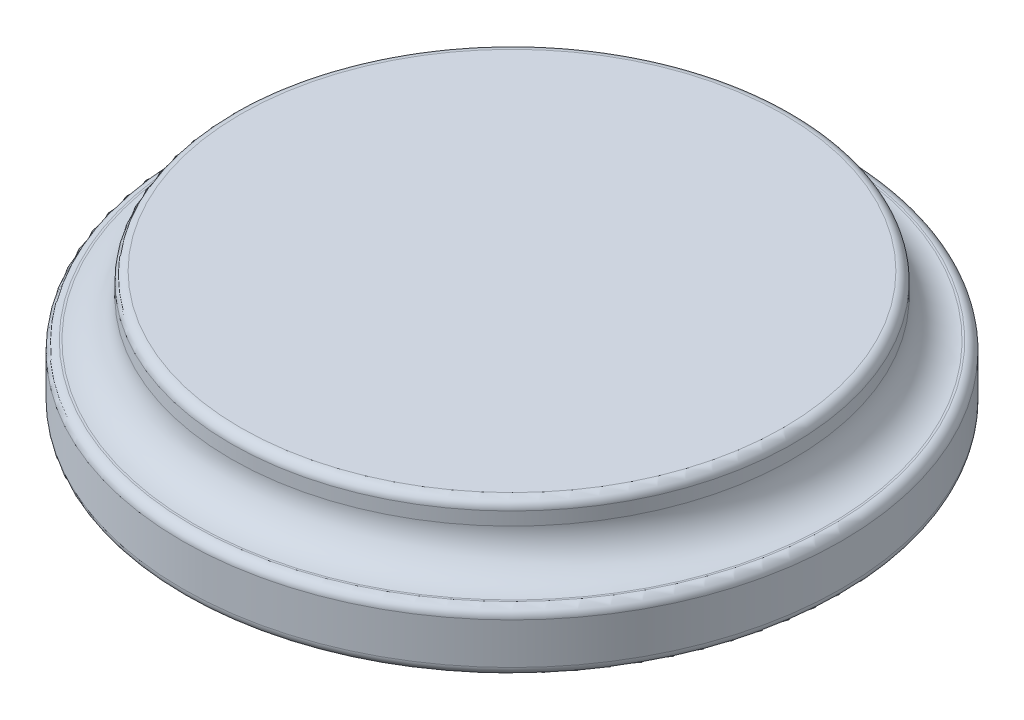
SolidWorks part; units mm, degrees
ref_plane "Front Plane" through (0, 0, 0) normal (0, 0, 1) x (1, 0, 0)
ref_plane "Top Plane" through (0, 0, 0) normal (0, 1, 0) x (1, 0, 0)
ref_plane "Right Plane" through (0, 0, 0) normal (1, 0, 0) x (0, 0, -1)
sketch "Sketch1" plane through (0, 0, 0) normal (0, 1, 0) x (1, 0, 0)
  circle A0 centre (0, 0) radius 17.6
  dimension "D1" = 35.2
extrude "Boss-Extrude1" add sketch "Sketch1" along normal blind 3.2
sketch "Sketch2" plane through (0, 3.2, 0) normal (0, 1, 0) x (1, 0, 0)
  circle A0 centre (0, 0) radius 15
  dimension "D1" = 30
extrude "Boss-Extrude2" add sketch "Sketch2" along normal blind 3.2
fillet "Fillet1" radius 2 1 edges at (0, 3.2, 15)
fillet "Fillet2" radius 0.5 1 edges at (0, 6.4, 15)
fillet "Fillet3" radius 0.5 1 edges at (0, 3.2, 17.6)
fillet "Fillet4" radius 0.5 1 edges at (0, 0, 17.6)
